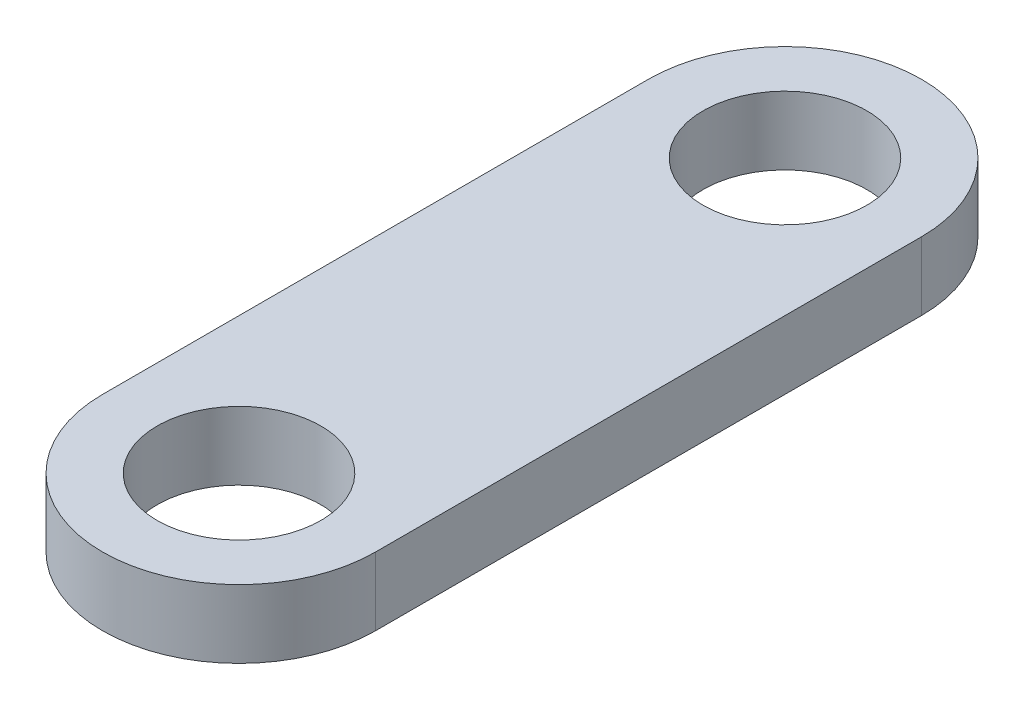
SolidWorks part; units mm, degrees
material "3D printed plastic"
ref_plane "Front Plane" through (0, 0, 0) normal (0, 0, 1) x (1, 0, 0)
ref_plane "Top Plane" through (0, 0, 0) normal (0, 1, 0) x (1, 0, 0)
ref_plane "Right Plane" through (0, 0, 0) normal (1, 0, 0) x (0, 0, -1)
sketch "Sketch1" plane through (0, 0, 0) normal (0, 1, 0) x (1, 0, 0)
  line L0 (0, 0) -> (0, -24) construction
  line L1 (6, 0) -> (6, -24)
  line L2 (-6, 0) -> (-6, -24)
  circle A0 centre (0, 0) radius 3.6
  circle A1 centre (0, -24) radius 3.6
  arc A2 (6, 0) -> (-6, 0) centre (0, 0) ccw
  arc A3 (-6, -24) -> (6, -24) centre (0, -24) ccw
  point P5 (0, -12)
  dimension "D1" = 0
  dimension "D2" = 24
  dimension "D3" = 7.2
  dimension "D5" = 7.2
  dimension "D4" = 12
extrude "Boss-Extrude1" add sketch "Sketch1" along normal blind 3
